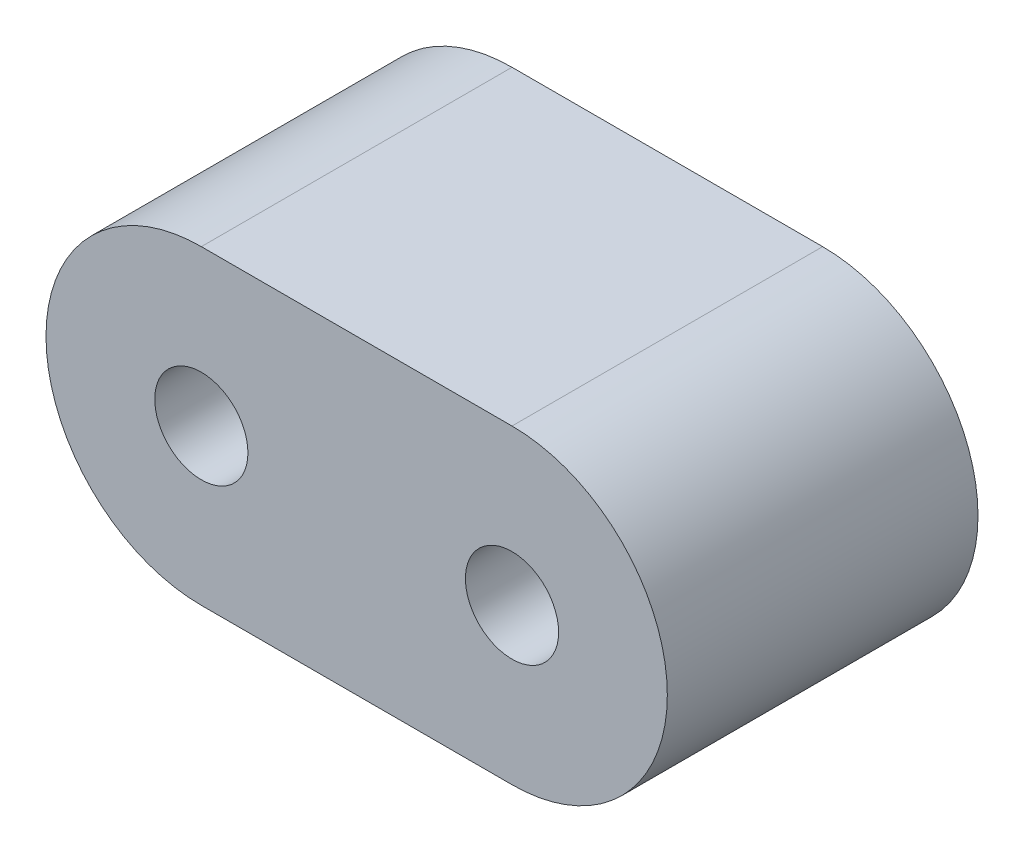
SolidWorks part; units mm, degrees
ref_plane "前视基准面" through (0, 0, 0) normal (0, 0, 1) x (1, 0, 0)
ref_plane "上视基准面" through (0, 0, 0) normal (0, 1, 0) x (1, 0, 0)
ref_plane "右视基准面" through (0, 0, 0) normal (1, 0, 0) x (0, 0, -1)
sketch "草图1" plane through (0, 0, 0) normal (0, 0, 1) x (1, 0, 0)
  line L0 (0, 0) -> (-10, 0) construction
  line L2 (0, -5) -> (-10, -5)
  line L3 (0, 5) -> (-10, 5)
  arc A0 (0, -5) -> (0, 5) centre (0, 0) ccw
  arc A1 (-10, 5) -> (-10, -5) centre (-10, 0) ccw
  point P5 (-5, 0)
extrude "凸台-拉伸1" add sketch "草图1" along normal blind 10
sketch "草图2" plane through (0, 0, 10) normal (0, 0, 1) x (1, 0, 0)
  circle A0 centre (0, 0) radius 1.5
  circle A1 centre (-10, 0) radius 1.5
  dimension "D1" = 3
  dimension "D2" = 3
extrude "切除-拉伸1" cut sketch "草图2" against normal blind 10
